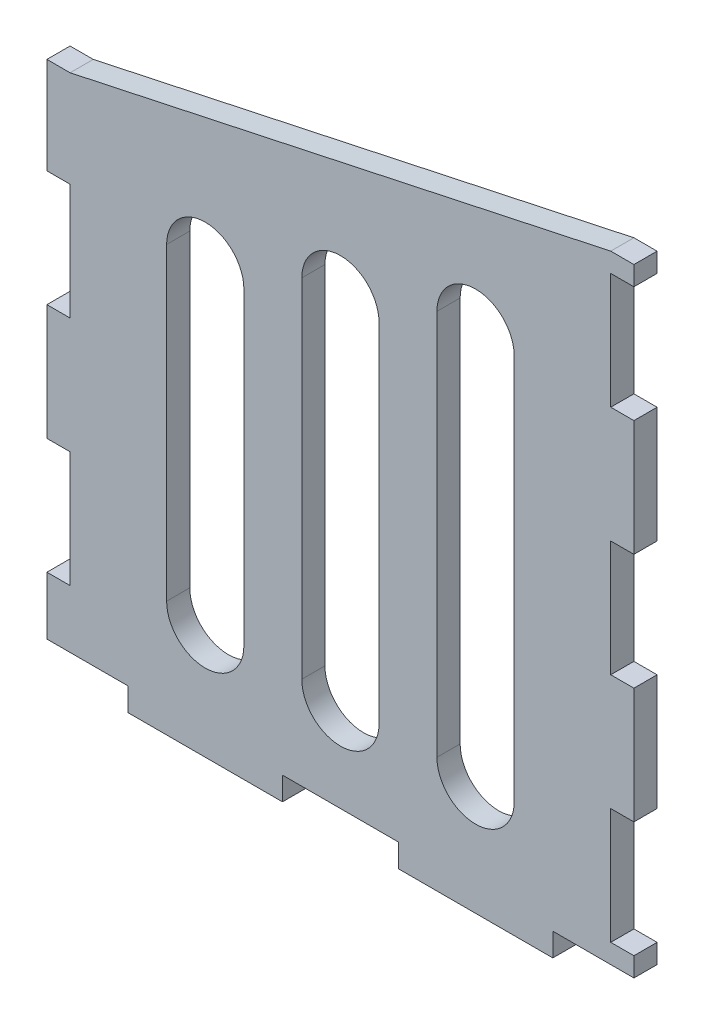
SolidWorks part; units mm, degrees
ref_plane "Front Plane" through (0, 0, 0) normal (0, 0, 1) x (1, 0, 0)
ref_plane "Top Plane" through (0, 0, 0) normal (0, 1, 0) x (1, 0, 0)
ref_plane "Right Plane" through (0, 0, 0) normal (1, 0, 0) x (0, 0, -1)
sketch "Sketch1" plane through (0, 0, 0) normal (0, 0, 1) x (1, 0, 0)
  line L0 (-35, 25) -> (35, 40)
  line L1 (38, -40) -> (-38, -40)
  line L2 (38, -40) -> (38, 40)
  line L3 (38, 40) -> (-38, 40)
  line L4 (-38, -40) -> (-38, 40)
  line L5 (38, -40) -> (-38, 40) construction
  line L6 (38, 40) -> (-38, -40) construction
  line L7 (-38, 25) -> (-35, 25)
  line L8 (35, 22.5) -> (38, 22.5)
  line L9 (35, 22.5) -> (35, 37.5)
  line L10 (35, 37.5) -> (38, 37.5)
  line L11 (38, 22.5) -> (38, 37.5)
  line L12 (35, 22.5) -> (38, 37.5) construction
  line L13 (35, 37.5) -> (38, 22.5) construction
  line L14 (35, -7.5) -> (38, -7.5)
  line L15 (35, -7.5) -> (35, 7.5)
  line L16 (35, 7.5) -> (38, 7.5)
  line L17 (38, -7.5) -> (38, 7.5)
  line L18 (35, -7.5) -> (38, 7.5) construction
  line L19 (35, 7.5) -> (38, -7.5) construction
  line L20 (-35, -32.5) -> (-38, -32.5)
  line L21 (-35, -32.5) -> (-35, -17.5)
  line L22 (-35, -17.5) -> (-38, -17.5)
  line L23 (-38, -32.5) -> (-38, -17.5)
  line L24 (-35, -32.5) -> (-38, -17.5) construction
  line L25 (-35, -17.5) -> (-38, -32.5) construction
  line L26 (27.5, -43) -> (7.5, -43)
  line L27 (27.5, -43) -> (27.5, -40)
  line L28 (27.5, -40) -> (7.5, -40)
  line L29 (7.5, -43) -> (7.5, -40)
  line L30 (27.5, -43) -> (7.5, -40) construction
  line L31 (27.5, -40) -> (7.5, -43) construction
  line L32 (-7.5, -43) -> (-27.5, -43)
  line L33 (-7.5, -43) -> (-7.5, -40)
  line L34 (-7.5, -40) -> (-27.5, -40)
  line L35 (-27.5, -43) -> (-27.5, -40)
  line L36 (-7.5, -43) -> (-27.5, -40) construction
  line L37 (-7.5, -40) -> (-27.5, -43) construction
  line L38 (35, -37.5) -> (38, -37.5)
  line L39 (35, -37.5) -> (35, -22.5)
  line L40 (35, -22.5) -> (38, -22.5)
  line L41 (38, -37.5) -> (38, -22.5)
  line L42 (35, -37.5) -> (38, -22.5) construction
  line L43 (35, -22.5) -> (38, -37.5) construction
  line L44 (-35, -2.5) -> (-38, -2.5)
  line L45 (-35, -2.5) -> (-35, 12.5)
  line L46 (-35, 12.5) -> (-38, 12.5)
  line L47 (-38, -2.5) -> (-38, 12.5)
  line L48 (-35, -2.5) -> (-38, 12.5) construction
  line L49 (-35, 12.5) -> (-38, -2.5) construction
  line L50 (-17.5, -28) -> (-17.5, 12) construction
  line L51 (-22.5, -28) -> (-22.5, 12)
  line L52 (-12.5, -28) -> (-12.5, 12)
  line L53 (17.5, -28) -> (17.5, 22) construction
  line L54 (12.5, -28) -> (12.5, 22)
  line L55 (22.5, -28) -> (22.5, 22)
  line L56 (0, 17) -> (0, -28) construction
  line L57 (5, 17) -> (5, -28)
  line L58 (-5, 17) -> (-5, -28)
  arc A0 (-22.5, -28) -> (-12.5, -28) centre (-17.5, -28) ccw
  arc A1 (-12.5, 12) -> (-22.5, 12) centre (-17.5, 12) ccw
  arc A2 (12.5, -28) -> (22.5, -28) centre (17.5, -28) ccw
  arc A3 (22.5, 22) -> (12.5, 22) centre (17.5, 22) ccw
  arc A4 (5, 17) -> (-5, 17) centre (0, 17) ccw
  arc A5 (-5, -28) -> (5, -28) centre (0, -28) ccw
  point P0 (0, 0)
  point P8 (36.5, 30)
  point P13 (36.5, 0)
  point P18 (-36.5, -25)
  point P23 (17.5, -41.5)
  point P28 (-17.5, -41.5)
  point P33 (-36.5, 5)
  point P34 (36.5, -30)
  point P46 (-17.5, -8)
  point P51 (17.5, -3)
  point P60 (0, -5.5)
  dimension "D17" = 5
  dimension "D18" = 5
  dimension "D21" = 5
  dimension "D1" = 76
  dimension "D2" = 80
  dimension "D3" = 3
  dimension "D4" = 65
  dimension "D5" = 3
  dimension "D6" = 15
  dimension "D7" = 15
  dimension "D8" = 15
  dimension "D9" = 3
  dimension "D10" = 15
  dimension "D11" = 7.5
  dimension "D12" = 3
  dimension "D13" = 20
  dimension "D14" = 15
  dimension "D15" = 7.5
  dimension "D16" = 15
  dimension "D19" = 40
  dimension "D20" = 50
  dimension "D22" = 45
  dimension "D23" = 12
extrude "Boss-Extrude1" add sketch "Sketch1" along normal blind 3
